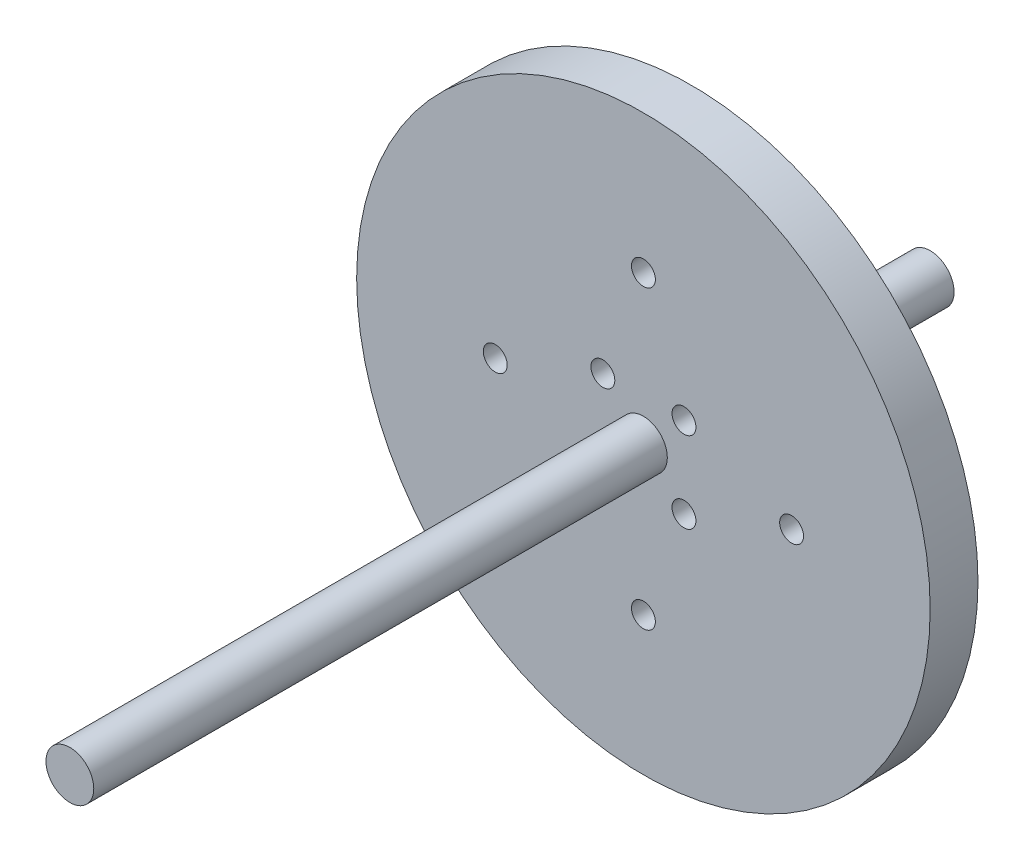
SolidWorks part; units mm, degrees
ref_plane "Front Plane" through (0, 0, 0) normal (0, 0, 1) x (1, 0, 0)
ref_plane "Top Plane" through (0, 0, 0) normal (0, 1, 0) x (1, 0, 0)
ref_plane "Right Plane" through (0, 0, 0) normal (1, 0, 0) x (0, 0, -1)
sketch "Sketch1" plane through (0, 0, 0) normal (0, 0, 1) x (1, 0, 0)
  circle A0 centre (0, 0) radius 30
extrude "Boss-Extrude1" add sketch "Sketch1" along normal blind 5
sketch "Sketch2" plane through (0, 0, 5) normal (0, 0, 1) x (1, 0, 0)
  line L0 (0, 15.5) -> (0, 0) construction
  line L1 (0, 0) -> (4.2426, 4.2426) construction
  circle A0 centre (0, 15.5) radius 1.25
  circle A1 centre (15.5, 0) radius 1.25
  circle A2 centre (0, -15.5) radius 1.25
  circle A3 centre (-15.5, 0) radius 1.25
  circle A4 centre (4.2426, 4.2426) radius 1.25
  circle A5 centre (4.2426, -4.2426) radius 1.25
  circle A6 centre (-4.2426, -4.2426) radius 1.25
  circle A7 centre (-4.2426, 4.2426) radius 1.25
  point P12 (0, 0)
  point P21 (0, 0)
  dimension "D1" = 15.5
  dimension "D3" = 2.5
  dimension "D4" = 2.5
  dimension "D5" = 6
  dimension "D7" = 45
  dimension "D2" = 4
  dimension "D6" = 4
extrude "Cut-Extrude1" cut sketch "Sketch2" against normal blind 5
sketch "Sketch3" plane through (0, 0, 0) normal (0, 0, -1) x (-1, 0, 0)
  circle A0 centre (0, 0) radius 2.5
extrude "Boss-Extrude2" add sketch "Sketch3" along normal blind 25
sketch "Sketch4" plane through (0, 0, 5) normal (0, 0, 1) x (1, 0, 0)
  circle A0 centre (0, 0) radius 2.5
extrude "Boss-Extrude3" add sketch "Sketch4" along normal blind 60
